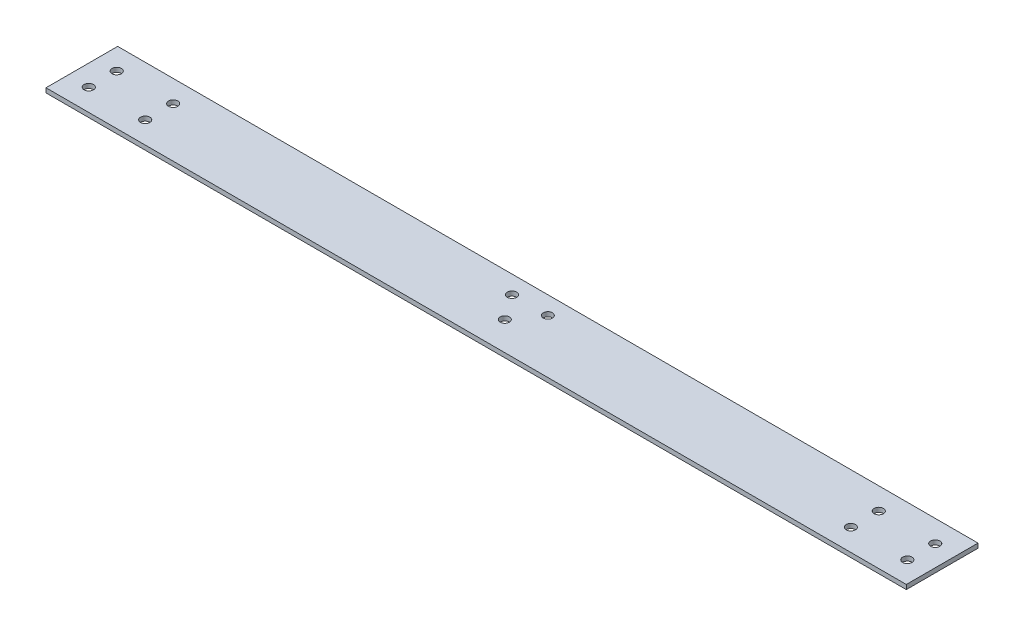
SolidWorks part; units mm, degrees
ref_plane "Front Plane" through (0, 0, 0) normal (0, 0, 1) x (1, 0, 0)
ref_plane "Top Plane" through (0, 0, 0) normal (0, 1, 0) x (1, 0, 0)
ref_plane "Right Plane" through (0, 0, 0) normal (1, 0, 0) x (0, 0, -1)
sketch "Sketch1" plane through (0, 0, 0) normal (0, 1, 0) x (1, 0, 0)
  line L0 (0, 0) -> (70.9902, 0) construction
  line L1 (-304.8, 25.4) -> (304.8, 25.4)
  line L2 (-304.8, 25.4) -> (-304.8, -25.4)
  line L3 (-304.8, -25.4) -> (304.8, -25.4)
  line L4 (304.8, 25.4) -> (304.8, -25.4)
  line L5 (-304.8, 25.4) -> (304.8, -25.4) construction
  line L6 (-304.8, -25.4) -> (304.8, 25.4) construction
  line L7 (0, 0) -> (0, -73.0667) construction
  circle A0 centre (-250, 9.9) radius 3.3
  circle A1 centre (-250, -9.9) radius 3.3
  circle A2 centre (-290, 9.9) radius 3.3
  circle A3 centre (-290, -9.9) radius 3.3
  circle A4 centre (290, -9.9) radius 3.3
  circle A5 centre (290, 9.9) radius 3.3
  circle A6 centre (250, -9.9) radius 3.3
  circle A7 centre (250, 9.9) radius 3.3
  point P0 (0, 0)
  dimension "D3" = 6.6
  dimension "D4" = 40
  dimension "D1" = 50.8
  dimension "D2" = 609.6
  dimension "D5" = 19.8
  dimension "D6" = 500
extrude "Boss-Extrude1" add sketch "Sketch1" along normal mid plane 3.175
sketch "Sketch2" plane through (0, 1.5875, 0) normal (0, 1, 0) x (1, 0, 0)
  line L0 (12.7, 12.7) -> (-12.7, 12.7) construction
  line L1 (304.8, 25.4) -> (-304.8, 25.4) construction
  circle A0 centre (-12.7, 12.7) radius 3.2639
  circle A1 centre (12.7, 12.7) radius 3.2639
  circle A2 centre (0, -5.08) radius 3.2639
  point P5 (0, 12.7)
  dimension "D1" = 12.7
  dimension "D3" = 6.5278
  dimension "D4" = 17.78
  dimension "D2" = 25.4
extrude "1/4-20 For Nut Bracket" cut sketch "Sketch2" against normal through all
